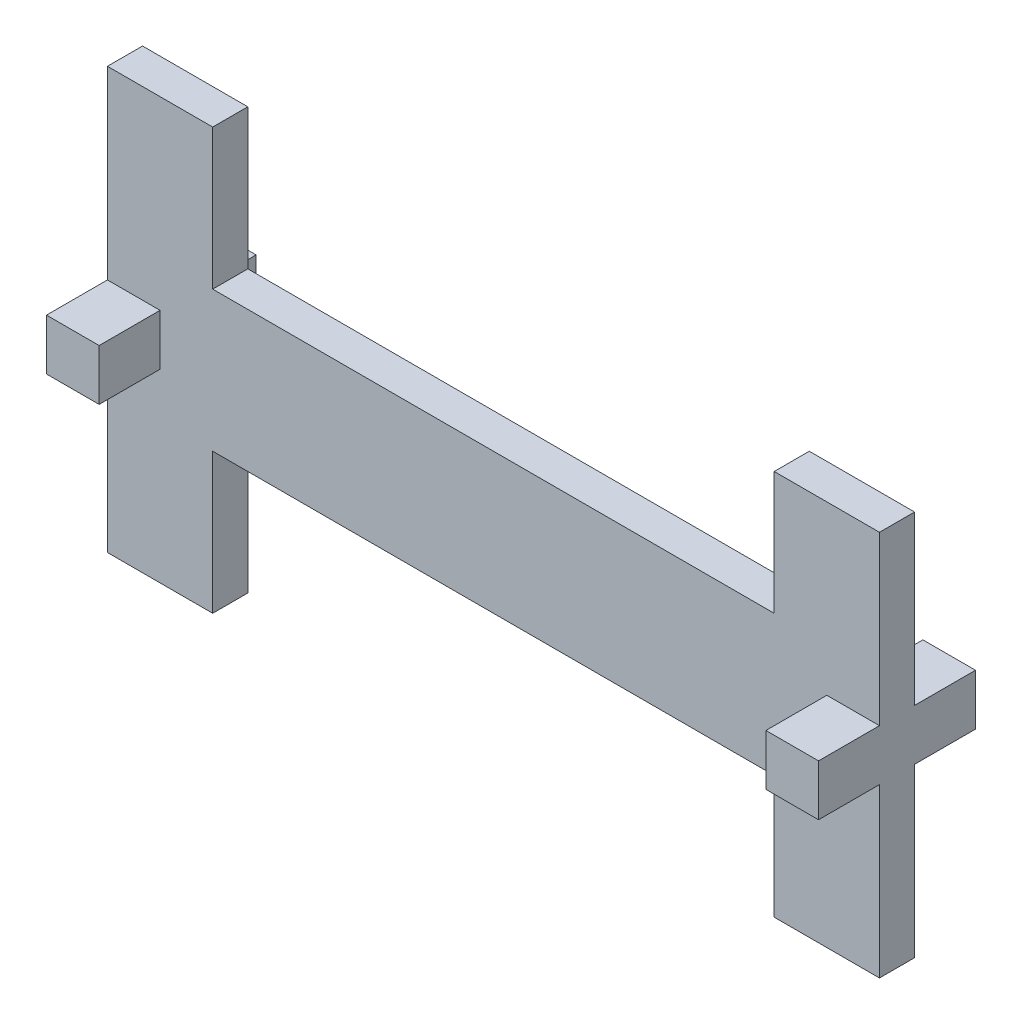
SolidWorks part; units mm, degrees
ref_plane "前视基准面" through (0, 0, 0) normal (0, 0, 1) x (1, 0, 0)
ref_plane "上视基准面" through (0, 0, 0) normal (0, 1, 0) x (1, 0, 0)
ref_plane "右视基准面" through (0, 0, 0) normal (1, 0, 0) x (0, 0, -1)
other "Configuration Table"
sketch "草图1" plane through (0, 0, 0) normal (0, 0, 1) x (1, 0, 0)
  line L1 (0, 0) -> (220, 0)
  line L2 (0, 0) -> (0, 120)
  line L3 (0, 120) -> (220, 120)
  line L4 (220, 0) -> (220, 120)
  dimension "D1" = 220
  dimension "D2" = 120
extrude "凸台-拉伸1" add sketch "草图1" along normal blind 10
sketch "草图2" plane through (0, 0, 10) normal (0, 0, 1) x (1, 0, 0)
  line L0 (0, 60) -> (220, 60) construction
  line L1 (0, 120) -> (0, 0) construction
  line L2 (220, 0) -> (220, 120) construction
  line L3 (30, 120) -> (30, 80)
  line L4 (220, 120) -> (0, 120) construction
  line L5 (30, 80) -> (190, 80)
  line L6 (190, 80) -> (190, 115)
  line L7 (190, 115) -> (220, 115)
  line L8 (190, 5) -> (220, 5)
  line L9 (190, 40) -> (190, 5)
  line L10 (30, 0) -> (30, 40)
  line L11 (30, 40) -> (190, 40)
  line L12 (0, 120) -> (0, 0)
  line L13 (0, 0) -> (220, 0)
  line L14 (220, 0) -> (220, 120)
  line L15 (220, 120) -> (0, 120)
  line L16 (0, 120) -> (0, 0)
  line L17 (0, 0) -> (220, 0)
  line L18 (220, 0) -> (220, 120)
  line L19 (220, 120) -> (0, 120)
  line M11 (0, 0) -> (220, 0)
  line M12 (220, 0) -> (220, 120)
  line M13 (220, 120) -> (0, 120)
  dimension "D1" = 0
  dimension "D2" = 30
  dimension "D3" = 30
  dimension "D4" = 5
  dimension "D5" = 20
extrude "切除-拉伸1" cut sketch "草图2" against normal blind 10 contours L6 L7 L3 L5 M12 M13 | L11 L10 L8 L9 M11 M12
sketch "草图5" plane through (220, 0, 0) normal (1, 0, 0) x (0, 0, -1)
  line L6 (-5, 135.084) -> (-5, -23.1189) construction
  line L24 (-52.8132, 60) -> (60.7826, 60) construction
  line L28 (-27.365, 67.27) -> (17.365, 67.27)
  line L29 (-27.365, 67.27) -> (-27.365, 52.73)
  line L30 (-27.365, 52.73) -> (17.365, 52.73)
  line L31 (17.365, 67.27) -> (17.365, 52.73)
  line L35 (0, 5) -> (0, 115)
  line L36 (0, 115) -> (-10, 115)
  line L37 (-10, 115) -> (-10, 5)
  line L38 (-10, 5) -> (0, 5)
  line L39 (0, 5) -> (0, 115)
  line L40 (0, 115) -> (-10, 115)
  line L41 (-10, 115) -> (-10, 5)
  line L42 (-10, 5) -> (0, 5)
  point P6 (-5, 8.9227)
  point P11 (-5, 115)
  point P13 (-27.365, 60)
  point P15 (0, 60)
  dimension "D2" = 44.73
  dimension "D3" = 0
  dimension "D1" = 14.54
extrude "凸台-拉伸2" add sketch "草图5" against normal blind 15
ref_plane "基准面1" through (110, 0, 0) normal (1, 0, 0) x (0, 0, -1)
mirror "镜向1" about plane through (110, 0, 0) normal (1, 0, 0) of "凸台-拉伸2"
